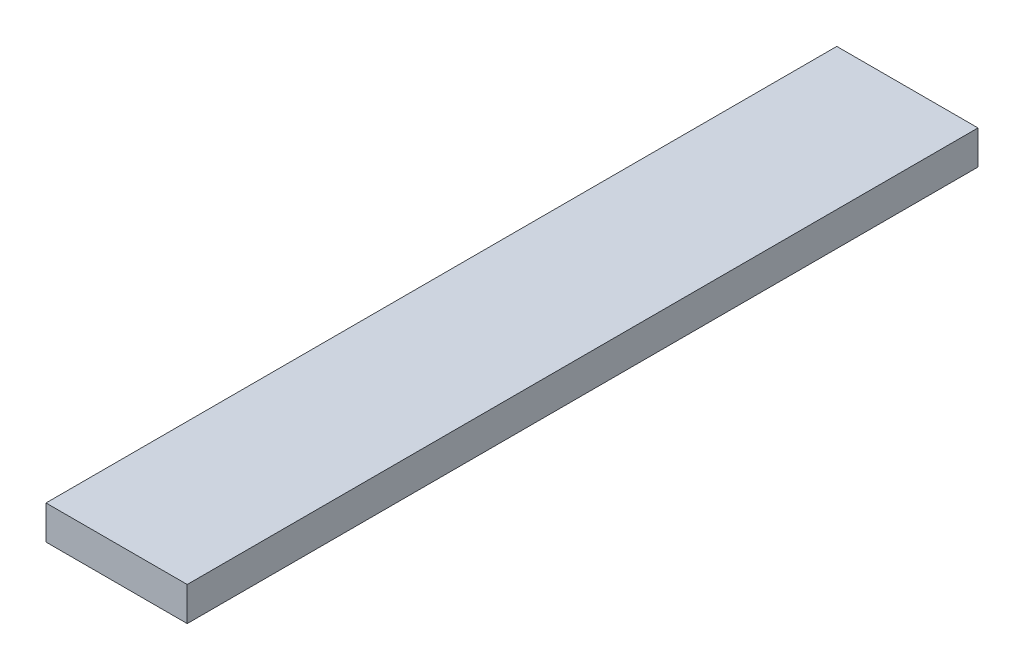
SolidWorks part; units mm, degrees
ref_plane "Alzado" through (0, 0, 0) normal (0, 0, 1) x (1, 0, 0)
ref_plane "Planta" through (0, 0, 0) normal (0, 1, 0) x (1, 0, 0)
ref_plane "Vista lateral" through (0, 0, 0) normal (1, 0, 0) x (0, 0, -1)
sketch "Croquis1" plane through (0, 0, 0) normal (0, 0, 1) x (1, 0, 0)
  line L1 (-12.5, -3) -> (12.5, -3)
  line L2 (-12.5, -3) -> (-12.5, 3)
  line L3 (-12.5, 3) -> (12.5, 3)
  line L4 (12.5, -3) -> (12.5, 3)
  line L5 (-12.5, -3) -> (12.5, 3) construction
  line L6 (-12.5, 3) -> (12.5, -3) construction
  point P0 (0, 0)
  dimension "D1" = 6
  dimension "D2" = 25
extrude "Saliente-Extruir1" add sketch "Croquis1" along normal blind 140
